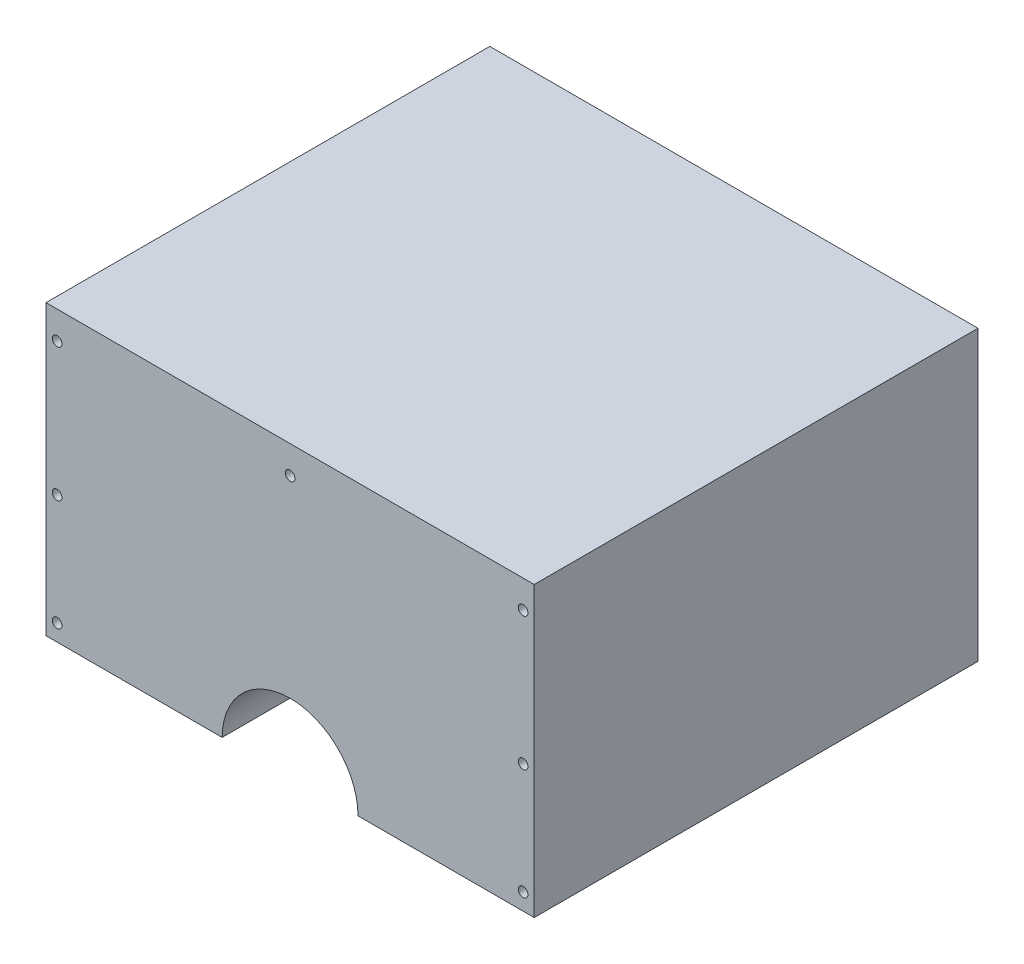
SolidWorks part; units mm, degrees
ref_plane "Front Plane" through (0, 0, 0) normal (0, 0, 1) x (1, 0, 0)
ref_plane "Top Plane" through (0, 0, 0) normal (0, 1, 0) x (1, 0, 0)
ref_plane "Right Plane" through (0, 0, 0) normal (1, 0, 0) x (0, 0, -1)
sketch "Sketch1" plane through (0, 0, 0) normal (0, 0, 1) x (1, 0, 0)
  line L1 (0, 0) -> (279.4, 0)
  line L2 (0, 0) -> (0, 165.1)
  line L3 (0, 165.1) -> (279.4, 165.1)
  line L4 (279.4, 0) -> (279.4, 165.1)
extrude "Boss-Extrude1" add sketch "Sketch1" along normal blind 254
sketch "Sketch2" plane through (0, 0, 0) normal (0, 0, 1) x (1, 0, 0)
  line L0 (0, 0) -> (279.4, 0) construction
  circle A0 centre (139.7, 0) radius 38.8874
extrude "Cut-Extrude1" cut sketch "Sketch2" along normal through all
sketch "Sketch3" plane through (0, 0, 0) normal (0, 0, 1) x (1, 0, 0)
  circle A0 centre (6.35, 149.225) radius 2.7686
  circle A1 centre (139.7, 149.225) radius 2.7686
  circle A2 centre (273.05, 149.225) radius 2.7686
  circle A3 centre (6.35, 73.025) radius 2.7686
  circle A4 centre (273.05, 73.025) radius 2.7686
  circle A5 centre (6.35, 9.525) radius 2.7686
  circle A6 centre (273.05, 9.525) radius 2.7686
extrude "Cut-Extrude2" cut sketch "Sketch3" along normal through all
